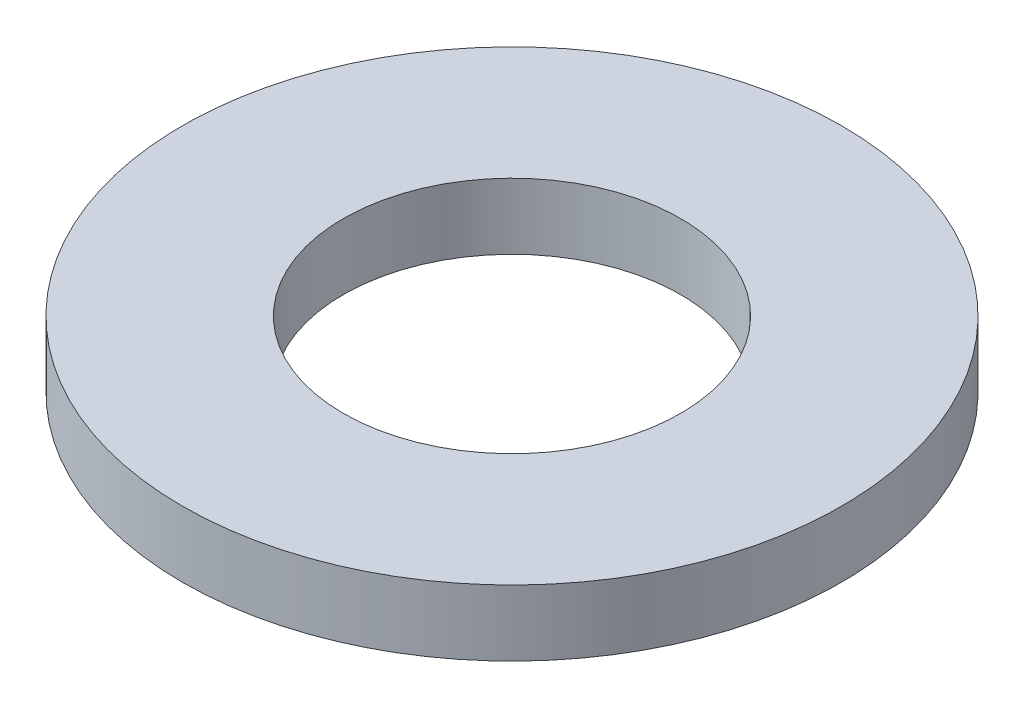
SolidWorks part; units mm, degrees
ref_plane "Front Plane" through (0, 0, 0) normal (0, 0, 1) x (1, 0, 0)
ref_plane "Top Plane" through (0, 0, 0) normal (0, 1, 0) x (1, 0, 0)
ref_plane "Right Plane" through (0, 0, 0) normal (1, 0, 0) x (0, 0, -1)
sketch "Sketch1" plane through (0, 0, 0) normal (0, 1, 0) x (1, 0, 0)
  circle A0 centre (0, 0) radius 3.2512
  circle A1 centre (0, 0) radius 6.35
extrude "Boss-Extrude1" add sketch "Sketch1" along normal blind 1.27
